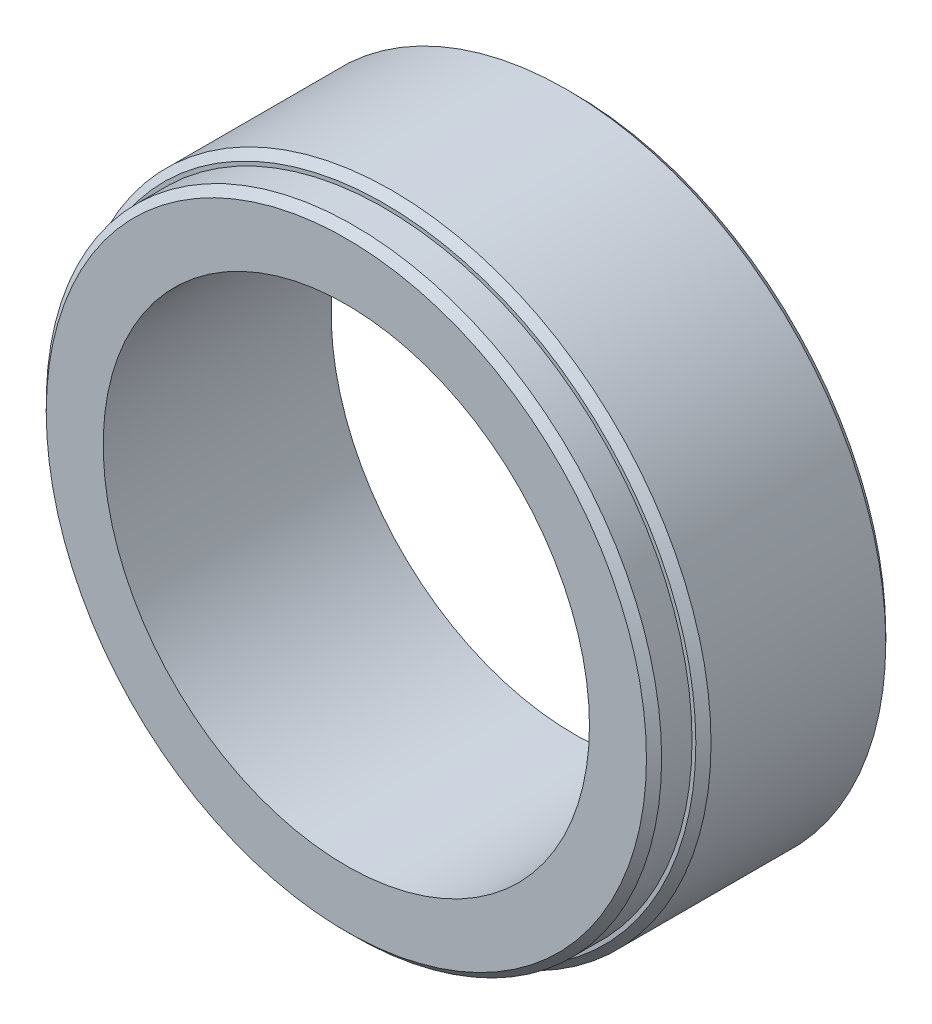
SolidWorks part; units mm, degrees
ref_plane "Front Plane" through (0, 0, 0) normal (0, 0, 1) x (1, 0, 0)
ref_plane "Top Plane" through (0, 0, 0) normal (0, 1, 0) x (1, 0, 0)
ref_plane "Right Plane" through (0, 0, 0) normal (1, 0, 0) x (0, 0, -1)
sketch "Sketch1" plane through (0, 0, 0) normal (0, 0, 1) x (1, 0, 0)
  circle A0 centre (0, 0) radius 32
  circle A1 centre (0, 0) radius 42
extrude "Boss-Extrude1" add sketch "Sketch1" along normal blind 25
sketch "Sketch2" plane through (0, 0, 25) normal (0, 0, 1) x (1, 0, 0)
  circle A0 centre (0, 0) radius 32
  circle A1 centre (0, 0) radius 40.5
extrude "Boss-Extrude2" add sketch "Sketch2" along normal blind 5
chamfer "Chamfer1" distance 1 angle 45 3 edges at (42, 0, 0) (42, 0, 25) (40.5, 0, 30)
